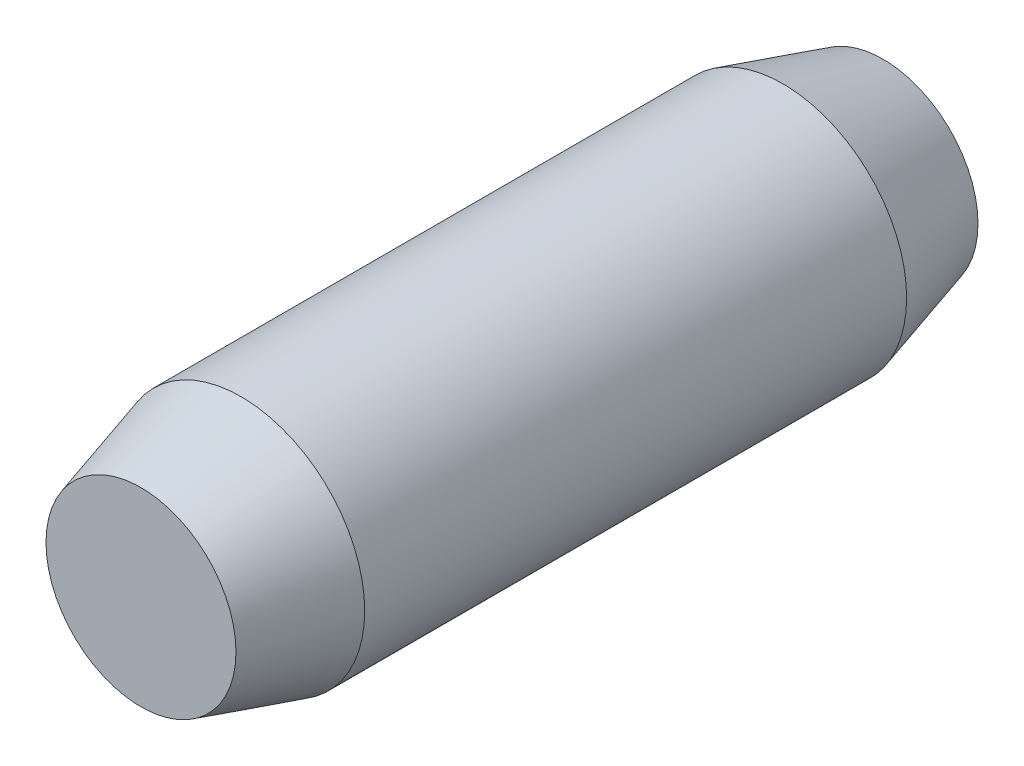
SolidWorks part; units mm, degrees
ref_plane "Front Plane" through (0, 0, 0) normal (0, 0, 1) x (1, 0, 0)
ref_plane "Top Plane" through (0, 0, 0) normal (0, 1, 0) x (1, 0, 0)
ref_plane "Right Plane" through (0, 0, 0) normal (1, 0, 0) x (0, 0, -1)
sketch "Sketch1" plane through (0, 0, 0) normal (0, 0, 1) x (1, 0, 0)
  circle A0 centre (0, 0) radius 0.7937
  point P3 (0, 0.7937)
  dimension "Diameter" = 1.5875
sketch "Sketch2" plane through (0, 0, 0) normal (1, 0, 0) x (0, 0, -1)
  line L0 (-2.3813, 0) -> (2.3813, 0) construction
  line L1 (-2.3813, 0) -> (-2.3813, 0.7937)
  line L2 (-2.3813, 0.7937) -> (2.3813, 0.7937)
  line L3 (2.3813, 0.7937) -> (2.3813, 0)
  line L4 (-2.3813, 0.6096) -> (-1.739, 0.7937)
  line L5 (2.3813, 0.6096) -> (1.739, 0.7937)
  dimension "Length" = 4.7625
  dimension "Chamfer Angle" = 16
  dimension "Point Diameter" = 1.2192
sketch "Sketch3" plane through (0, 0, 0) normal (1, 0, 0) x (0, 0, -1)
  line L0 (-2.3813, 0) -> (2.3813, 0) construction
  line L1 (2.3813, 0.7937) -> (2.3813, 0) construction
  line L2 (-2.3813, 0.7937) -> (2.3813, 0.7937) construction
  line L3 (-2.3813, 0) -> (-2.3813, 0.7937) construction
  line L4 (-2.3813, 0) -> (2.3813, 0)
  line L5 (2.3813, 0.6096) -> (2.3813, 0)
  line L6 (-1.739, 0.7937) -> (1.739, 0.7937)
  line L7 (-2.3813, 0) -> (-2.3813, 0.6096)
  line L8 (2.3813, 0.6096) -> (1.739, 0.7937) construction
  line L9 (-2.3813, 0.6096) -> (-1.739, 0.7937) construction
  line L10 (2.3813, 0.6096) -> (1.739, 0.7937)
  line L11 (-2.3813, 0.6096) -> (-1.739, 0.7937)
revolve "Revolve1" add sketch "Sketch3" angle 360 about L0
